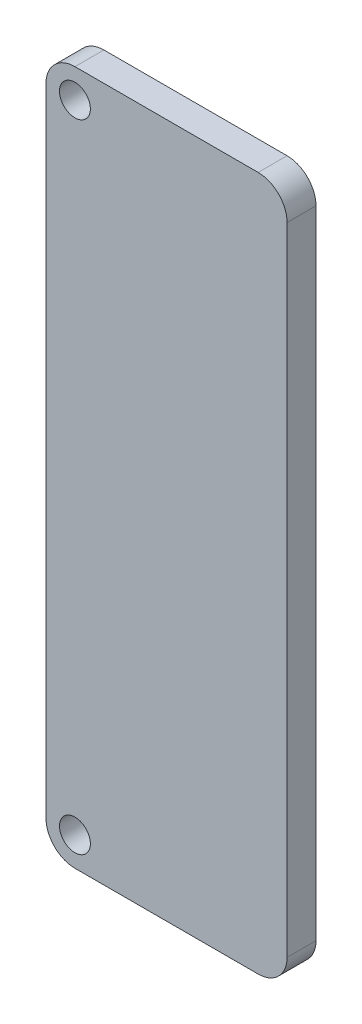
SolidWorks part; units mm, degrees
ref_plane "Front Plane" through (0, 0, 0) normal (0, 0, 1) x (1, 0, 0)
ref_plane "Top Plane" through (0, 0, 0) normal (0, 1, 0) x (1, 0, 0)
ref_plane "Right Plane" through (0, 0, 0) normal (1, 0, 0) x (0, 0, -1)
sketch "Sketch1" plane through (0, 0, 0) normal (0, 0, 1) x (1, 0, 0)
  line L0 (0, 36) -> (0, -36)
  line L1 (0, -36) -> (-22, -36)
  line L3 (0, 36) -> (-22, 36)
  line L4 (-25, -33) -> (-25, 33)
  line L5 (0, 0) -> (-25, 36) construction
  line L6 (0, 0) -> (-25, -36) construction
  arc A0 (-25, -33) -> (-22, -36) centre (-22, -33) ccw
  arc A1 (-25, 33) -> (-22, 36) centre (-22, 33) cw
  circle A2 centre (-22, 33) radius 1.6
  circle A3 centre (-22, -33) radius 1.6
  point P0 (0, 0)
  dimension "D1" = 3
  dimension "D4" = 3.2
  dimension "D2" = 72
  dimension "D3" = 25
extrude "Boss-Extrude1" add sketch "Sketch1" along normal blind 3
fillet "Fillet1" radius 3 2 edges at (0, 36, 1.5) (0, -36, 1.5)
